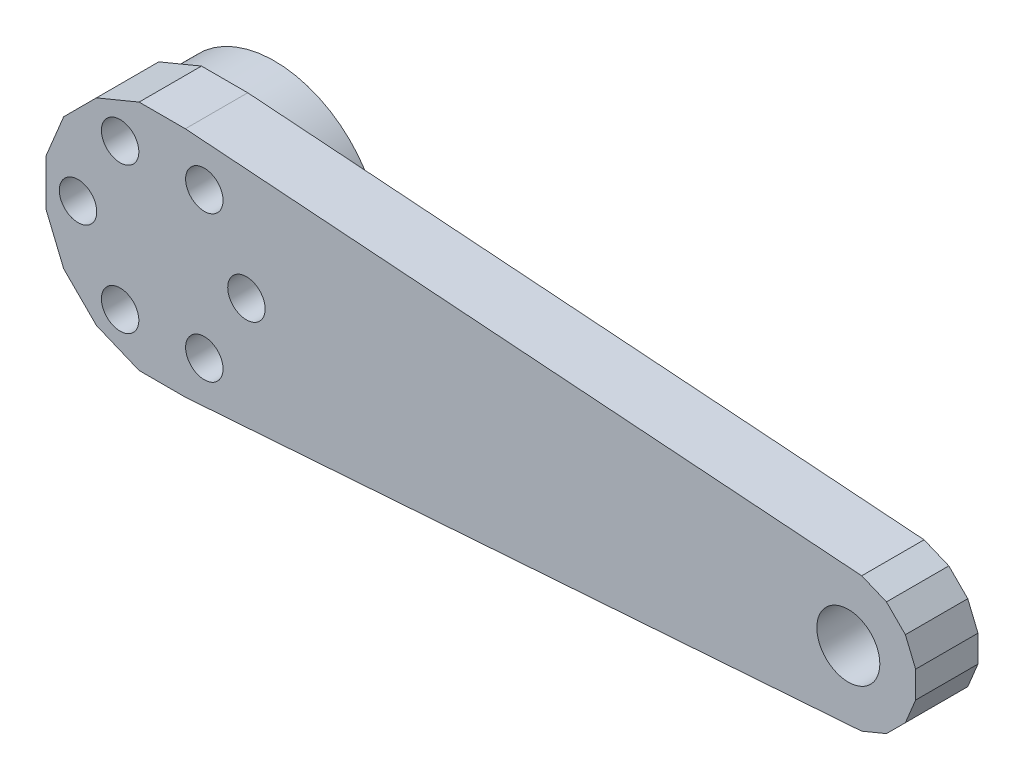
SolidWorks part; units mm, degrees
ref_plane "前视基准面" through (0, 0, 0) normal (0, 0, 1) x (1, 0, 0)
ref_plane "上视基准面" through (0, 0, 0) normal (0, 1, 0) x (1, 0, 0)
ref_plane "右视基准面" through (0, 0, 0) normal (1, 0, 0) x (0, 0, -1)
other "Configuration Table"
sketch "Profile_1" plane through (0, 0, 0) normal (0, 0, 1) x (1, 0, 0)
  line L0 (112.146, 10.7886) -> (3.7067, 18.6349)
  line L1 (3.7067, 18.6349) -> (-3.7067, 18.6349)
  line L2 (-3.7067, 18.6349) -> (-10.5558, 15.7979)
  line L3 (-10.5558, 15.7979) -> (-15.7979, 10.5558)
  line L4 (-15.7979, 10.5558) -> (-18.6349, 3.7067)
  line L5 (-18.6349, 3.7067) -> (-18.6349, -3.7067)
  line L6 (-18.6349, -3.7067) -> (-15.7979, -10.5558)
  line L7 (-15.7979, -10.5558) -> (-10.5558, -15.7979)
  line L8 (-10.5558, -15.7979) -> (-3.7067, -18.6349)
  line L9 (-3.7067, -18.6349) -> (3.7067, -18.6349)
  line L10 (3.7067, -18.6349) -> (112.146, -10.7886)
  line L11 (112.146, -10.7886) -> (116.1113, -9.1462)
  line L12 (116.1113, -9.1462) -> (119.1462, -6.1113)
  line L13 (119.1462, -6.1113) -> (120.7886, -2.146)
  line L14 (120.7886, -2.146) -> (120.7886, 2.146)
  line L15 (120.7886, 2.146) -> (119.1462, 6.1113)
  line L16 (119.1462, 6.1113) -> (116.1113, 9.1462)
  line L17 (116.1113, 9.1462) -> (112.146, 10.7886)
  circle A0 centre (110, 0) radius 5.05
  circle A1 centre (13.5, 0) radius 1.65
  circle A2 centre (6.75, 11.6913) radius 1.65
  circle A3 centre (-6.75, 11.6913) radius 1.65
  circle A4 centre (-13.5, 0) radius 1.65
  circle A5 centre (-6.75, -11.6913) radius 1.65
  circle A6 centre (6.75, -11.6913) radius 1.65
extrude "Arm_web" add sketch "Profile_1" along normal blind 10 from offset 8
sketch "Profile_2" plane through (0, 0, 0) normal (0, 0, 1) x (1, 0, 0)
  circle A0 centre (0, 0) radius 17.2
  circle A1 centre (0, 0) radius 5
  circle A2 centre (13.5, 0) radius 1.65
  circle A3 centre (6.75, 11.6913) radius 1.65
  circle A4 centre (-6.75, 11.6913) radius 1.65
  circle A5 centre (-13.5, 0) radius 1.65
  circle A6 centre (-6.75, -11.6913) radius 1.65
  circle A7 centre (6.75, -11.6913) radius 1.65
extrude "Rotor_standoff" add sketch "Profile_2" along normal blind 8 from offset 0
sketch "Profile_3" plane through (0, 0, 0) normal (0, 0, 1) x (1, 0, 0)
  circle A0 centre (13.5, 0) radius 3
  circle A1 centre (6.75, 11.6913) radius 3
  circle A2 centre (-6.75, 11.6913) radius 3
  circle A3 centre (-13.5, 0) radius 3
  circle A4 centre (-6.75, -11.6913) radius 3
  circle A5 centre (6.75, -11.6913) radius 3
extrude "Rotor_screw_spotfaces" cut sketch "Profile_3" along normal blind 6.01 from offset 12
